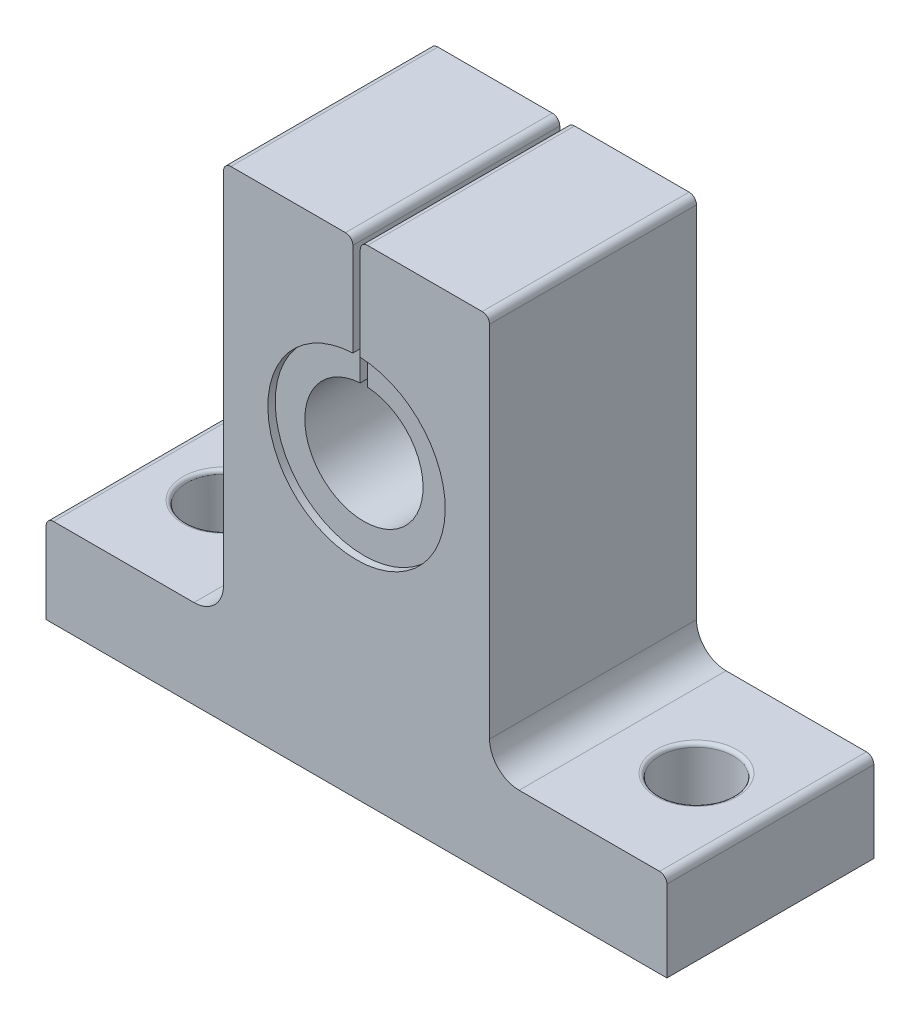
SolidWorks part; units mm, degrees
material "7050-T73510"
ref_plane "Front Plane" through (0, 0, 0) normal (0, 0, 1) x (1, 0, 0)
ref_plane "Top Plane" through (0, 0, 0) normal (0, 1, 0) x (1, 0, 0)
ref_plane "Right Plane" through (0, 0, 0) normal (1, 0, 0) x (0, 0, -1)
sketch "Sketch1" plane through (0, 0, 0) normal (0, 0, 1) x (1, 0, 0)
  line L0 (0, 0) -> (0, 32.8) construction
  line L1 (21, 0) -> (-21, 0)
  line L2 (-21, 0) -> (-21, 6)
  line L3 (-21, 6) -> (-9, 6)
  line L4 (-9, 6) -> (-9, 32.8)
  line L5 (-9, 32.8) -> (9, 32.8)
  line L6 (9, 6) -> (9, 32.8)
  line L7 (21, 6) -> (9, 6)
  line L8 (21, 0) -> (21, 6)
  dimension "D1" = 18
  dimension "D2" = 32.8
  dimension "D3" = 6
  dimension "D4" = 42
extrude "Boss-Extrude1" add sketch "Sketch1" along normal blind 14
sketch "Sketch2" plane through (0, 0, 14) normal (0, 0, 1) x (1, 0, 0)
  line L0 (0, 16) -> (0, 0) construction
  circle A0 centre (0, 20) radius 4
  dimension "D1" = 8
  dimension "D2" = 20
extrude "Cut-Extrude1" cut sketch "Sketch2" against normal through all
sketch "Sketch3" plane through (0, 0, 14) normal (0, 0, 1) x (1, 0, 0)
  circle A0 centre (0, 20) radius 6
  dimension "D1" = 12
extrude "Cut-Extrude2" cut sketch "Sketch3" against normal blind 0.5
sketch "Sketch4" plane through (0, 0, 0) normal (0, 0, -1) x (-1, 0, 0)
  circle A0 centre (0, 20) radius 6
  dimension "D1" = 12
extrude "Cut-Extrude3" cut sketch "Sketch4" against normal blind 0.5
sketch "Sketch5" plane through (0, 6, 0) normal (0, 1, 0) x (1, 0, 0)
  line L0 (0, 0) -> (0, -19.4521) construction
  line L1 (-21, -7) -> (21, -7) construction
  line L2 (-21, -14) -> (-21, 0) construction
  line L3 (21, -14) -> (21, 0) construction
  circle A0 centre (-16, -7) radius 2.5
  circle A1 centre (16, -7) radius 2.5
  dimension "D1" = 5
  dimension "D2" = 32
extrude "Cut-Extrude4" cut sketch "Sketch5" against normal through all
sketch "Sketch6" plane through (0, 32.8, 0) normal (0, 1, 0) x (1, 0, 0)
  line L0 (-9, 0) -> (9, -14) construction
  line L1 (9, 0) -> (-9, -14) construction
  line L2 (9, -14) -> (-9, -14) construction
  line L3 (-0.25, 0) -> (0.25, 0)
  line L4 (-0.25, 0) -> (-0.25, -14)
  line L5 (-0.25, -14) -> (0.25, -14)
  line L6 (0.25, 0) -> (0.25, -14)
  line L7 (-0.25, 0) -> (0.25, -14) construction
  line L8 (-0.25, -14) -> (0.25, 0) construction
  point P8 (0, -7)
  dimension "D1" = 0.5
sketch "Sketch7" plane through (0, 32.8, 0) normal (0, 1, 0) x (1, 0, 0)
  line L1 (0.25, -14) -> (-0.25, -14)
  line L2 (0.25, -14) -> (0.25, 0)
  line L3 (0.25, 0) -> (-0.25, 0)
  line L4 (-0.25, -14) -> (-0.25, 0)
  line L5 (0.25, -14) -> (-0.25, 0) construction
  line L6 (0.25, 0) -> (-0.25, -14) construction
  point P0 (0, -7)
extrude "Cut-Extrude5" cut sketch "Sketch7" against normal up to surface (8.8078 mm away)
fillet "Fillet1" radius 2 2 edges at (9, 6, 7) (-9, 6, 7)
fillet "Fillet2" radius 0.5 6 edges at (-9, 32.8, 7) (9, 32.8, 7) (-21, 6, 7) (21, 6, 7) (-0.25, 32.8, 7) (0.25, 32.8, 7)
fillet "Fillet3" radius 0.25 2 edges at (16, 6, 4.5) (-16, 6, 9.5)
